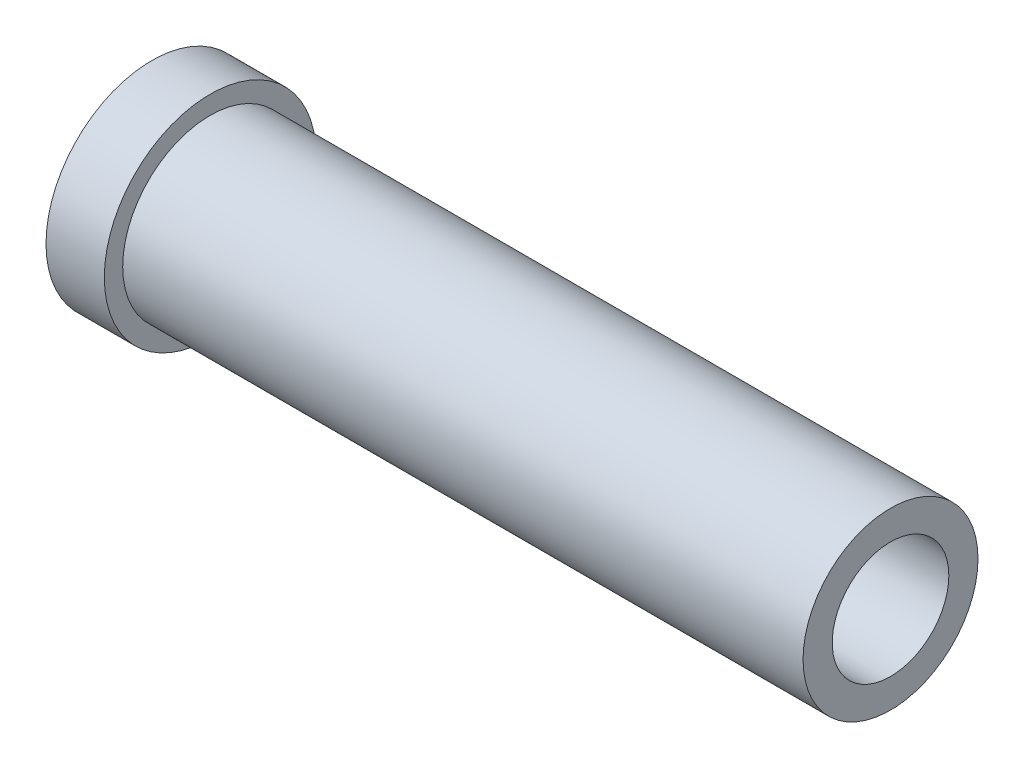
SolidWorks part; units mm, degrees
ref_plane "Plan de face" through (0, 0, 0) normal (0, 0, 1) x (1, 0, 0)
ref_plane "Plan de dessus" through (0, 0, 0) normal (0, 1, 0) x (1, 0, 0)
ref_plane "Plan de droite" through (0, 0, 0) normal (1, 0, 0) x (0, 0, -1)
sketch "Esquisse1" plane through (0, 0, 0) normal (1, 0, 0) x (0, 0, -1)
  circle A0 centre (0, 0) radius 4.5
  circle A1 centre (0, 0) radius 3
extrude "Extrusion1" add sketch "Esquisse1" along normal blind 38
sketch "Esquisse2" plane through (0, 0, 0) normal (-1, 0, 0) x (0, 0, 1)
  circle A0 centre (0, 0) radius 4.5 construction
  circle A1 centre (0, 0) radius 4.5
  circle A2 centre (0, 0) radius 5.4455
extrude "Extrusion2" add sketch "Esquisse2" against normal blind 3
